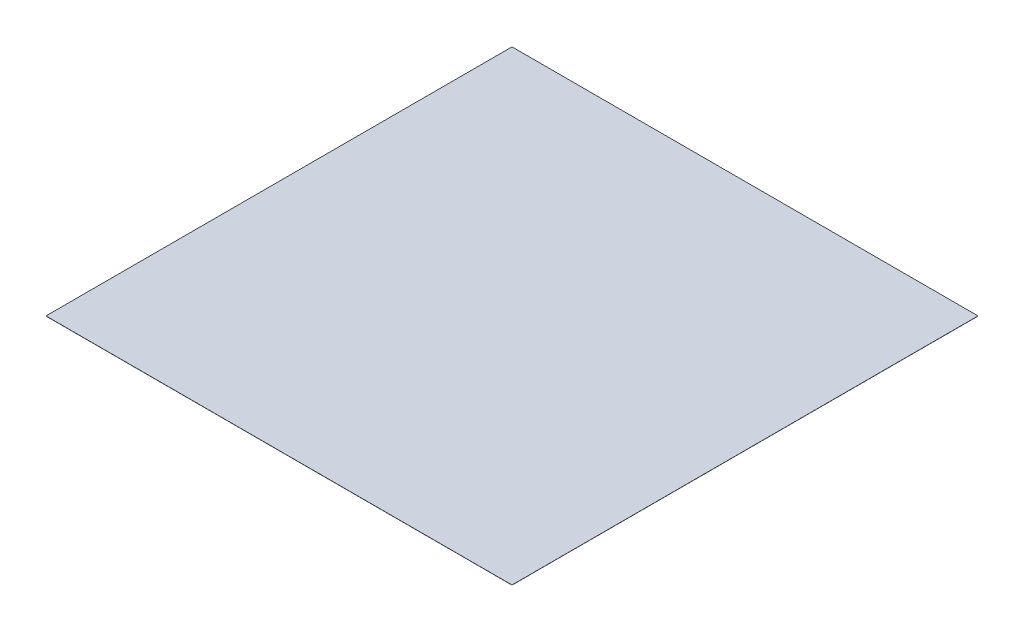
SolidWorks part; units mm, degrees
ref_plane "Plano frontal" through (0, 0, 0) normal (0, 0, 1) x (1, 0, 0)
ref_plane "Plano superior" through (0, 0, 0) normal (0, 1, 0) x (1, 0, 0)
ref_plane "Plano direito" through (0, 0, 0) normal (1, 0, 0) x (0, 0, -1)
sketch "Esboço1" plane through (0, 0, 0) normal (0, 1, 0) x (1, 0, 0)
  line L0 (-1093, 595.536) -> (-1073, 595.536)
  line L1 (0, 0) -> (18.9344, 0)
  line L2 (0, 0) -> (0, 766.8662)
  line L3 (0, 766.8662) -> (18.9344, 766.8662)
  line L4 (18.9344, 0) -> (18.9344, 766.8662)
  line L5 (-381.6968, 766.8662) -> (-362.7624, 766.8662)
  line L6 (-381.6968, 766.8662) -> (-381.6968, 345.536)
  line L7 (-381.6968, 345.536) -> (-362.7624, 345.536)
  line L8 (-362.7624, 766.8662) -> (-362.7624, 345.536)
  line L9 (-858.9344, 645.536) -> (-840, 645.536)
  line L10 (-858.9344, 645.536) -> (-858.9344, 345.536)
  line L11 (-858.9344, 345.536) -> (-840, 345.536)
  line L12 (-840, 645.536) -> (-840, 345.536)
  line L13 (-853.5858, 925.2213) -> (-1253.5858, 925.2213)
  line L14 (-853.5858, 925.2213) -> (-853.5858, 945.2213)
  line L15 (-853.5858, 945.2213) -> (-1253.5858, 945.2213)
  line L16 (-1253.5858, 925.2213) -> (-1253.5858, 945.2213)
  line L17 (-1093, 595.536) -> (-1093, 195.536)
  line L18 (-1093, 195.536) -> (-1073, 195.536)
  line L19 (-1073, 595.536) -> (-1073, 195.536)
  line L21 (-858.9344, 427.7897) -> (-1250.0103, 427.7897)
  line L23 (-858.9344, 407.7897) -> (-1250.0103, 407.7897)
  line L24 (-1250.0103, 427.7897) -> (-1250.0103, 407.7897)
  line L33 (-1439.6613, 239.7512) -> (-1560.0448, 239.7512)
  line L34 (-1439.6613, 239.7512) -> (-1439.6613, 219.7512)
  line L35 (-1439.6613, 219.7512) -> (-1560.0448, 219.7512)
  line L36 (-1560.0448, 239.7512) -> (-1560.0448, 219.7512)
  line L37 (-1627.2015, 576.144) -> (-1607.2015, 576.144)
  line L38 (-1627.2015, 576.144) -> (-1627.2015, 317.0654)
  line L39 (-1627.2015, 317.0654) -> (-1607.2015, 317.0654)
  line L40 (-1607.2015, 576.144) -> (-1607.2015, 317.0654)
  line L41 (-1627.2015, 769.6927) -> (-1607.2015, 769.6927)
  line L42 (-1627.2015, 769.6927) -> (-1627.2015, 1019.6927)
  line L43 (-1627.2015, 1019.6927) -> (-1607.2015, 1019.6927)
  line L44 (-1607.2015, 769.6927) -> (-1607.2015, 1019.6927)
  line L69 (-864.2122, 399.5244) -> (-894.2122, 399.5244)
  line L70 (-864.2122, 399.5244) -> (-864.2122, 369.5244)
  line L71 (-864.2122, 369.5244) -> (-894.2122, 369.5244)
  line L72 (-894.2122, 399.5244) -> (-894.2122, 369.5244)
  arc A6 (-381.6968, 766.8662) -> (18.9344, 766.8662) centre (-181.3812, 766.8662) cw
  arc A7 (-362.7624, 766.8662) -> (0, 766.8662) centre (-181.3812, 766.8662) cw
  arc A8 (-362.7624, 345.536) -> (-858.9344, 345.536) centre (-610.8484, 345.536) cw
  arc A9 (-381.6968, 345.536) -> (-840, 345.536) centre (-610.8484, 345.536) cw
  arc A10 (-840, 645.536) -> (-803.6955, 702.0415) centre (-777.8744, 645.536) cw
  arc A11 (-803.6955, 702.0415) -> (-853.5858, 945.2213) centre (-856.6336, 817.8884) ccw
  arc A12 (-858.9344, 645.536) -> (-814.4955, 717.9247) centre (-777.7563, 645.536) cw
  arc A13 (-814.4955, 717.9247) -> (-853.5858, 925.2213) centre (-864.2122, 815.8835) ccw
  arc A14 (-1093, 595.536) -> (-1188.5366, 677.9223) centre (-1176.2913, 595.536) ccw
  arc A15 (-1188.5366, 677.9223) -> (-1354.3411, 742.8189) centre (-1214.8489, 854.9525) cw
  arc A16 (-1354.3411, 742.8189) -> (-1253.5858, 945.2213) centre (-1257.3278, 820.805) cw
  arc A17 (-1073, 595.536) -> (-1188.5366, 698.0004) centre (-1176.2038, 595.536) ccw
  arc A18 (-1188.5366, 698.0004) -> (-1341.8208, 766.8662) centre (-1207.9995, 859.705) cw
  arc A19 (-1341.8208, 766.8662) -> (-1253.5858, 925.2213) centre (-1258.876, 824.4093) cw
  arc A22 (-1368.7558, 309.7722) -> (-1439.6613, 219.7512) centre (-1474.849, 320.402) cw
  arc A23 (-1388.5562, 309.7722) -> (-1439.6613, 239.7512) centre (-1477.6183, 321.1143) cw
  arc A24 (-1388.5562, 309.7722) -> (-1250.0103, 427.7897) centre (-1254.4723, 292.6965) cw
  arc A25 (-1607.2015, 317.0654) -> (-1560.0448, 239.7512) centre (-1520.2441, 317.0654) ccw
  arc A26 (-1627.2015, 317.0654) -> (-1560.0448, 219.7512) centre (-1523.1159, 317.0654) ccw
  arc A27 (-1368.7558, 309.7722) -> (-1250.0103, 407.7897) centre (-1259.9289, 298.8686) cw
  point P69 (0, 0)
extrude "Ressalto-extrusão20" add sketch "Esboço1" along normal blind 0.01 contours L71 L72 L69 L70
